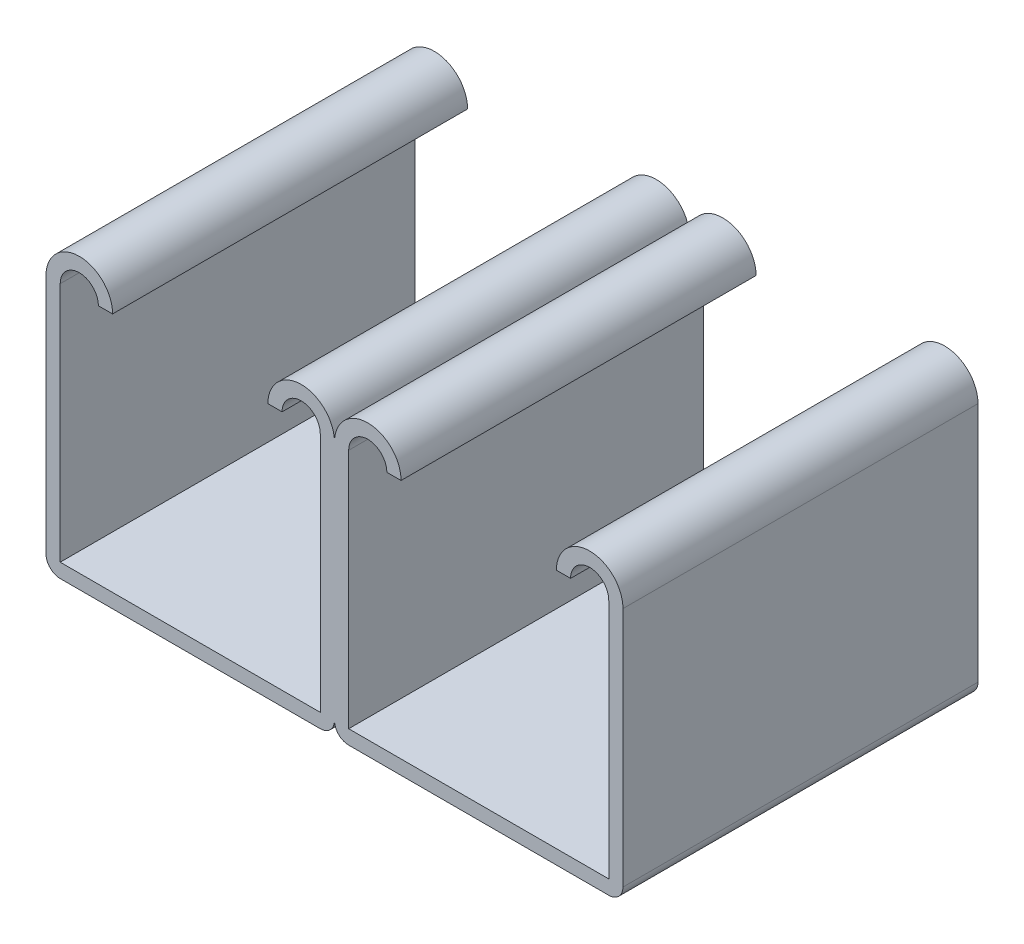
SolidWorks part; units mm, degrees
ref_plane "Plane1" through (0, 0, 0) normal (0, 0, 1) x (1, 0, 0)
ref_plane "Plane2" through (0, 0, 0) normal (0, 1, 0) x (1, 0, 0)
ref_plane "Plane3" through (0, 0, 0) normal (1, 0, 0) x (0, 0, -1)
sketch "Sketch1" plane through (0, 0, 0) normal (0, 0, 1) x (1, 0, 0)
  line L0 (-20.6375, 9.3789) -> (-20.6375, -7.874)
  line L1 (-19.6215, -8.89) -> (-1.016, -8.89)
  line L2 (0, -7.874) -> (0, 9.3789)
  line L6 (-19.6215, 9.3789) -> (-19.6215, -7.874)
  line L7 (-19.6215, -7.874) -> (-1.016, -7.874)
  line L8 (-1.016, -7.874) -> (-1.016, 9.3789)
  line L10 (-44.483, 11.7602) -> (25.4, 11.7602) construction
  line L12 (-16.891, 9.3789) -> (-15.875, 9.3789)
  line L13 (-4.7625, 9.3789) -> (-3.7465, 9.3789)
  arc A0 (0, 9.3789) -> (-4.7625, 9.3789) centre (-2.3813, 9.3789) ccw
  arc A1 (-20.6375, 9.3789) -> (-15.875, 9.3789) centre (-18.2563, 9.3789) cw
  arc A2 (-19.6215, -8.89) -> (-20.6375, -7.874) centre (-19.6215, -7.874) cw
  arc A3 (-1.016, -8.89) -> (0, -7.874) centre (-1.016, -7.874) ccw
  arc A4 (-19.6215, 9.3789) -> (-16.891, 9.3789) centre (-18.2563, 9.3789) cw
  arc A5 (-1.016, 9.3789) -> (-3.7465, 9.3789) centre (-2.3813, 9.3789) ccw
  dimension "D1" = 1.016
  dimension "Width" = 20.6375
  dimension "D5" = 8.89
  dimension "D8" = 11.7602
  dimension "D2" = 4.7625
  dimension "D3" = 11.1125
  dimension "D4" = 4.7625
  dimension "D6" = 1.016
  dimension "gauge" = 1.016
extrude "Base-Extrude" add sketch "Sketch1" along normal mid plane 25.4
pattern_linear "LPattern1" count 2 spacing 20.6375 along (1, 0, 0) of "Base-Extrude"
equation "\"D1@Sketch1\" = \"gauge@Sketch1\""
